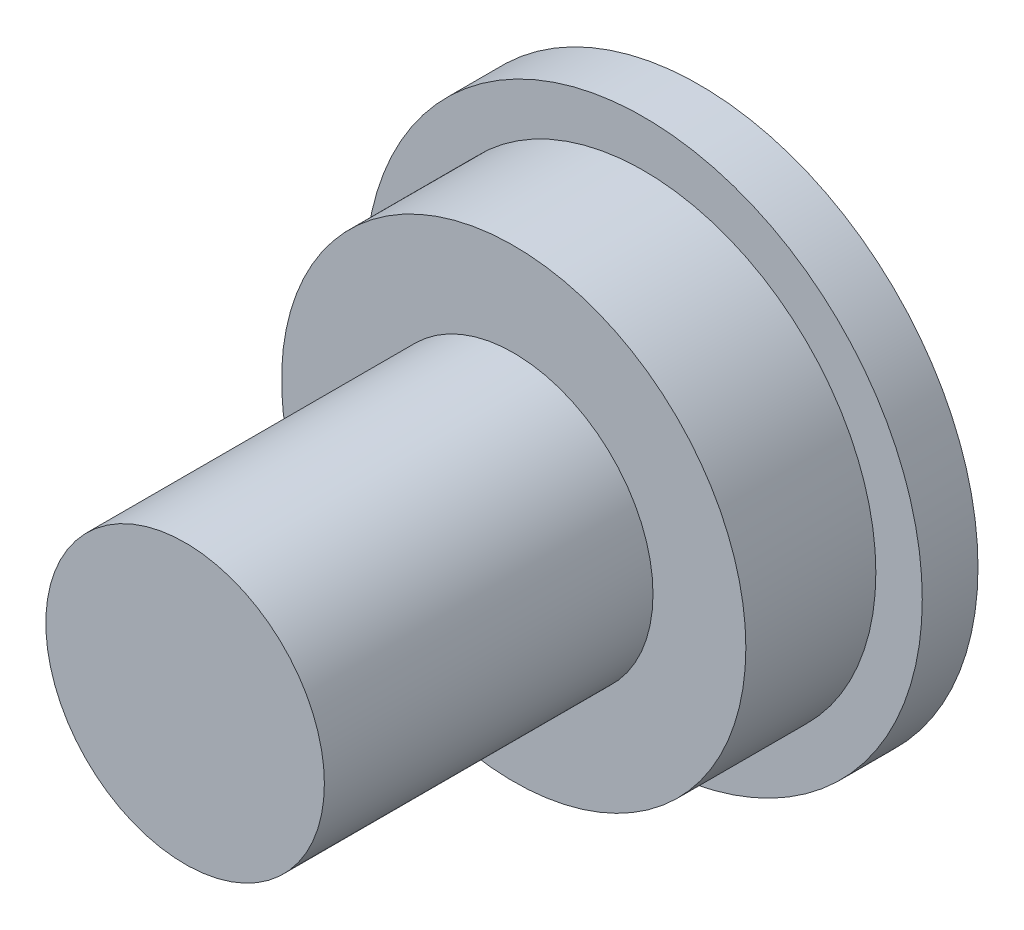
SolidWorks part; units mm, degrees
ref_plane "Front Plane" through (0, 0, 0) normal (0, 0, 1) x (1, 0, 0)
ref_plane "Top Plane" through (0, 0, 0) normal (0, 1, 0) x (1, 0, 0)
ref_plane "Right Plane" through (0, 0, 0) normal (1, 0, 0) x (0, 0, -1)
sketch "Sketch2" plane through (0, 0, 0) normal (0, 0, 1) x (1, 0, 0)
  circle A0 centre (0, 0) radius 15
  dimension "D1" = 30
extrude "Boss-Extrude1" add sketch "Sketch2" along normal blind 10
ref_plane "Plane1" through (0, 0, 10) normal (0, 0, 1) x (1, 0, 0)
sketch "Sketch3" plane through (0, 0, 10) normal (0, 0, 1) x (1, 0, 0)
  circle A0 centre (0, 0) radius 12.5
  circle A1 centre (0, 0) radius 15
  dimension "D1" = 25
extrude "Cut-Extrude1" cut sketch "Sketch3" against normal blind 7
sketch "Sketch4" plane through (0, 0, 10) normal (0, 0, 1) x (1, 0, 0)
  circle A0 centre (0, 0) radius 7.5
  dimension "D1" = 15
extrude "Boss-Extrude4" add sketch "Sketch4" along normal blind 17.695
